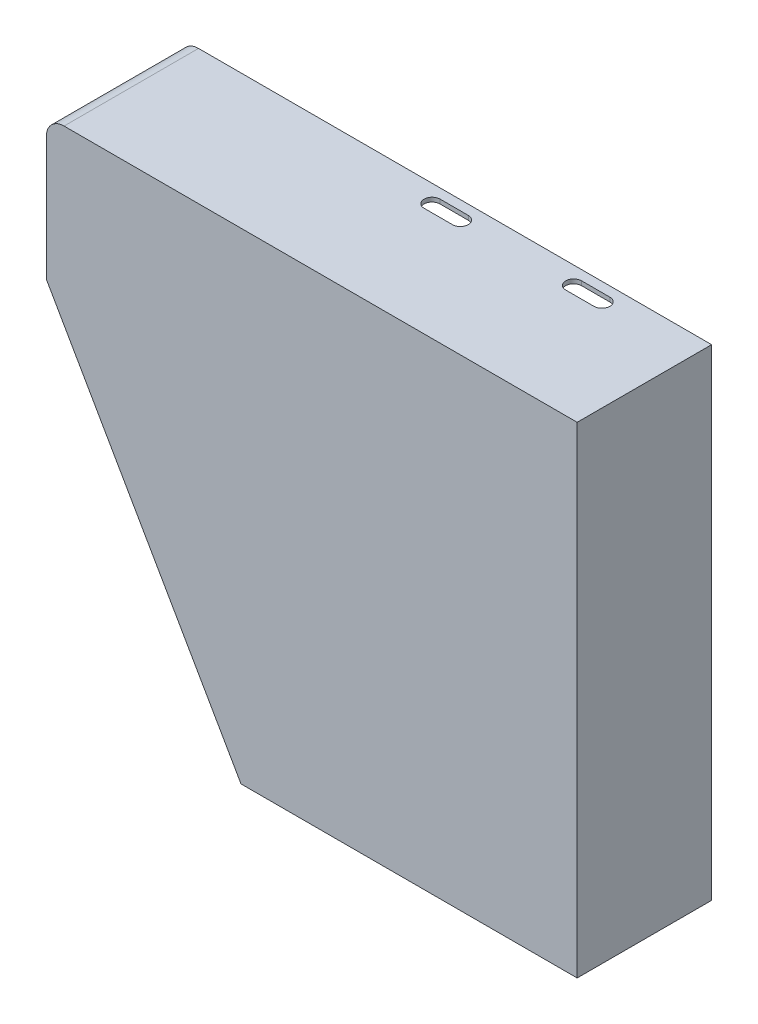
SolidWorks part; units mm, degrees
ref_plane "前视基准面" through (0, 0, 0) normal (0, 0, 1) x (1, 0, 0)
ref_plane "上视基准面" through (0, 0, 0) normal (0, 1, 0) x (1, 0, 0)
ref_plane "右视基准面" through (0, 0, 0) normal (1, 0, 0) x (0, 0, -1)
sketch "草图1" plane through (0, 0, 0) normal (0, 0, 1) x (1, 0, 0)
  line L0 (-150, 96) -> (-95, 0)
  line L1 (0, 0) -> (-95, 0)
  line L2 (0, 136) -> (0, 0)
  line L3 (-145, 136) -> (0, 136)
  line L4 (-150, 96) -> (-150, 131)
  line L5 (-1.2, 1.2) -> (-94.3045, 1.2) construction
  line L6 (-1.2, 134.8) -> (-1.2, 1.2) construction
  line L7 (-143.8, 134.8) -> (-1.2, 134.8) construction
  line L8 (-148.8, 96.3194) -> (-148.8, 129.8) construction
  line L9 (-148.8, 96.3194) -> (-94.3045, 1.2) construction
  line L10 (-66, 0) -> (-66, 1.2) construction
  line L11 (-66, 134.8) -> (-66, 136) construction
  line L12 (-26, 0) -> (-26, 1.2) construction
  line L13 (-26, 134.8) -> (-26, 136) construction
  line L14 (-74, 0) -> (-74, 1.2) construction
  line L15 (-34, 0) -> (-34, 1.2) construction
  line L16 (-74, 134.8) -> (-74, 136) construction
  line L17 (-34, 134.8) -> (-34, 136) construction
  line L18 (-63.75, 0) -> (-63.75, 1.2) construction
  line L19 (-63.75, 134.8) -> (-63.75, 136) construction
  line L20 (-23.75, 0) -> (-23.75, 1.2) construction
  line L21 (-23.75, 134.8) -> (-23.75, 136) construction
  line L22 (-76.25, 1.2) -> (-76.25, 0) construction
  line L23 (-36.25, 1.2) -> (-36.25, 0) construction
  line L24 (-76.25, 136) -> (-76.25, 134.8) construction
  line L25 (-36.25, 136) -> (-36.25, 134.8) construction
  line L26 (-70, 131.4256) -> (-70, 139.3364) construction
  line L27 (-30, 131.4256) -> (-30, 139.3364) construction
  line L28 (-70, 4.5744) -> (-70, -3.3364) construction
  line L29 (-30, 4.5744) -> (-30, -3.3364) construction
  arc A0 (-145, 136) -> (-150, 131) centre (-145, 131) ccw
  arc A1 (-143.8, 134.8) -> (-148.8, 129.8) centre (-143.8, 129.8) ccw construction
extrude "凸台-拉伸1" add sketch "草图1" along normal blind 38
shell "抽壳1" thickness 1.2
sketch "草图3" plane through (0, 0, 0) normal (0, -1, 0) x (1, 0, 0)
  line L0 (-150, 0) -> (-150, 38)
  line L1 (-135, 38) -> (-135, 0)
  line L2 (-150, 38) -> (-135, 38)
  line L3 (-135, 0) -> (-150, 0)
  line L4 (-3, 0) -> (-3, 38)
  line L5 (-135, 38) -> (-3, 38)
  line L6 (-74, 2.75) -> (-66, 2.75)
  line L7 (-66, 7.25) -> (-74, 7.25)
  line L8 (-34, 2.75) -> (-26, 2.75)
  line L9 (-26, 7.25) -> (-34, 7.25)
  line L10 (-135, 0) -> (-3, 0)
  line L11 (0, 38) -> (0, 0)
  line L12 (-3, 38) -> (0, 38)
  line L13 (0, 0) -> (-3, 0)
  line L14 (-148.8, 0) -> (-148.8, 36.8) construction
  line L15 (-148.8, 36.8) -> (-135, 36.8) construction
  line L16 (-135, 36.8) -> (-135, 0) construction
  line L17 (-1.2, 36.8) -> (-1.2, 0) construction
  line L18 (-3, 36.8) -> (-1.2, 36.8) construction
  line L19 (-3, 0) -> (-3, 36.8) construction
  line L20 (-135, 36.8) -> (-3, 36.8) construction
  line L21 (-94.8231, 36.8) -> (-94.8231, 0) construction
  line L22 (-3, 38) -> (-3, 0) construction
  line L23 (-93.2613, 0) -> (-93.2613, 36.8) construction
  line L24 (-95.8643, 38) -> (-95.8643, 0) construction
  line L25 (-93.2613, 0) -> (-93.2613, 38) construction
  arc A0 (-66, 2.75) -> (-66, 7.25) centre (-66, 5) ccw
  arc A1 (-74, 7.25) -> (-74, 2.75) centre (-74, 5) ccw
  arc A2 (-26, 2.75) -> (-26, 7.25) centre (-26, 5) ccw
  arc A3 (-34, 7.25) -> (-34, 2.75) centre (-34, 5) ccw
extrude "切除-拉伸1" cut sketch "草图3" against normal through all both and the other way through all contours L7 A1 L6 A0 | L9 A3 L8 A2
